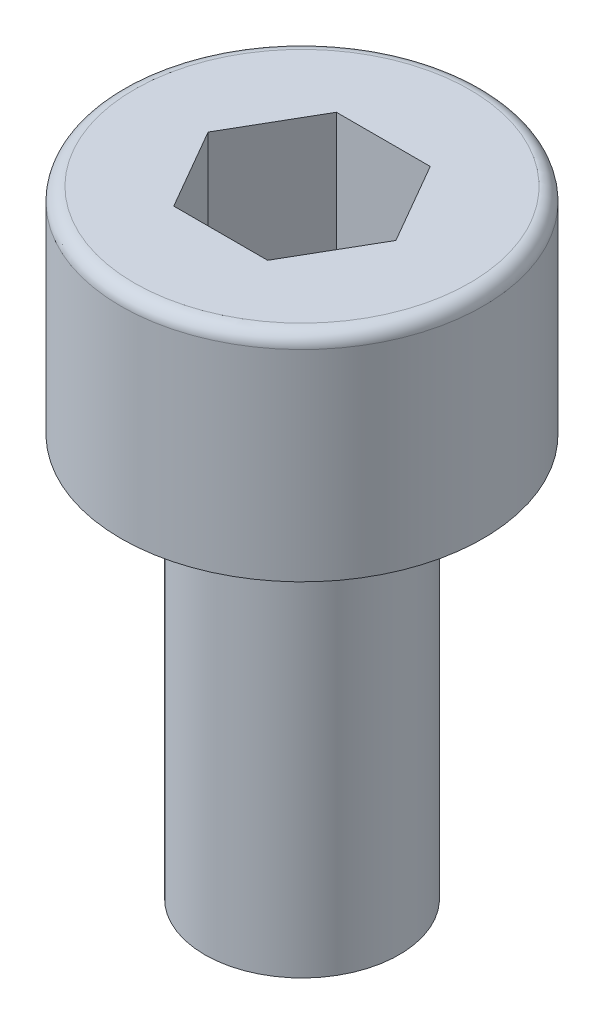
SolidWorks part; units mm, degrees
ref_plane "Front Plane" through (0, 0, 0) normal (0, 0, 1) x (1, 0, 0)
ref_plane "Top Plane" through (0, 0, 0) normal (0, 1, 0) x (1, 0, 0)
ref_plane "Right Plane" through (0, 0, 0) normal (1, 0, 0) x (0, 0, -1)
sketch "Sketch1" plane through (0, 0, 0) normal (0, 1, 0) x (1, 0, 0)
  circle A0 centre (0, 0) radius 2.7
  dimension "D1" = 5.4
extrude "Boss-Extrude1" add sketch "Sketch1" along normal blind 3.2
sketch "Sketch2" plane through (0, 3.2, 0) normal (0, 1, 0) x (1, 0, 0)
  line L1 (1.4, 0) -> (0.7, 1.2124)
  line L2 (0.7, 1.2124) -> (-0.7, 1.2124)
  line L3 (-0.7, 1.2124) -> (-1.4, 0)
  line L4 (-1.4, 0) -> (-0.7, -1.2124)
  line L5 (-0.7, -1.2124) -> (0.7, -1.2124)
  line L6 (0.7, -1.2124) -> (1.4, 0)
  circle A0 centre (0, 0) radius 1.2124 construction
  dimension "D1" = 2.8
extrude "Cut-Extrude1" cut sketch "Sketch2" against normal blind 2
fillet "Fillet1" radius 0.2 1 edges at (0, 3.2, 2.7)
sketch "Sketch3" plane through (0, 0, 0) normal (0, -1, 0) x (1, 0, 0)
  circle A0 centre (0, 0) radius 1.45
  dimension "D1" = 2.9
extrude "Boss-Extrude3" add sketch "Sketch3" along normal blind 6
